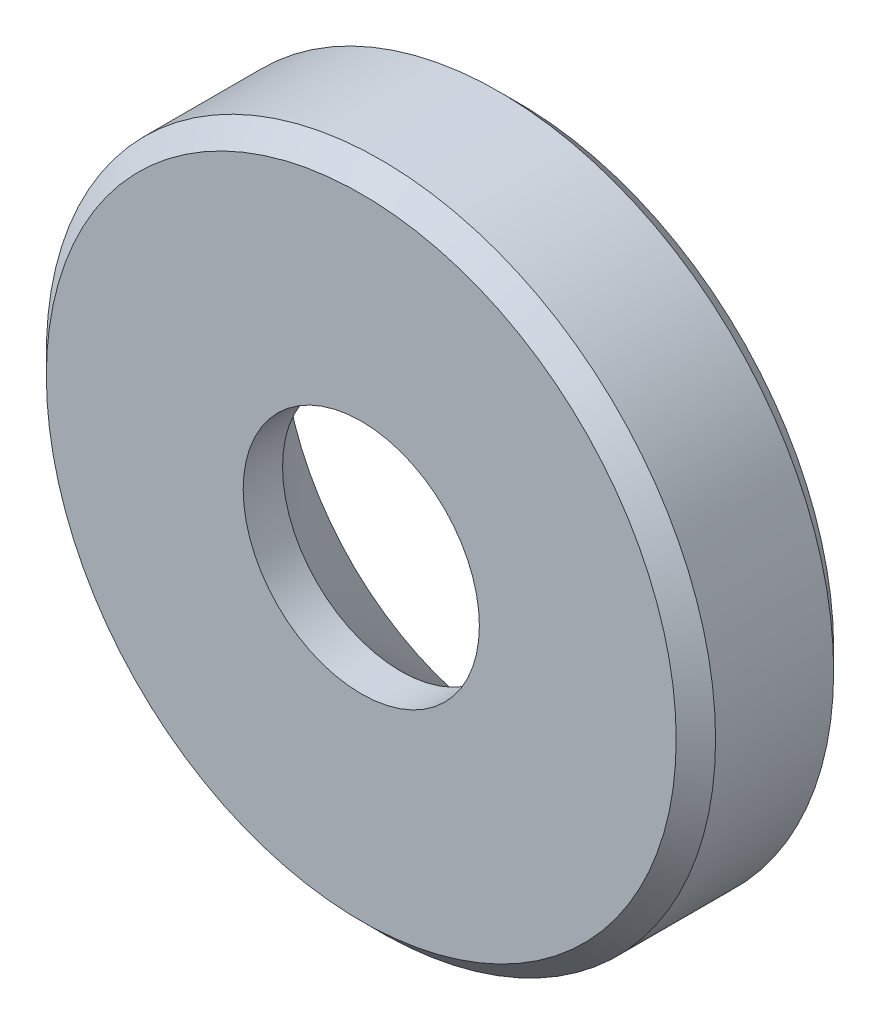
SolidWorks part; units mm, degrees
ref_plane "Front Plane" through (0, 0, 0) normal (0, 0, 1) x (1, 0, 0)
ref_plane "Top Plane" through (0, 0, 0) normal (0, 1, 0) x (1, 0, 0)
ref_plane "Right Plane" through (0, 0, 0) normal (1, 0, 0) x (0, 0, -1)
sketch "Sketch1" plane through (0, 0, 0) normal (0, 0, 1) x (1, 0, 0)
  circle A0 centre (0, 0) radius 17
extrude "Boss-Extrude2" add sketch "Sketch1" along normal blind 8
sketch "Sketch3" plane through (0, 0, 0) normal (0, 1, 0) x (1, 0, 0)
  line L0 (0, 0) -> (0, -8)
  line L1 (-17, -8) -> (17, -8) construction
  line L2 (0, -8) -> (6, -8)
  line L3 (6, -8) -> (6, -6)
  line L4 (6, -6) -> (12, 0)
  line L5 (17, 0) -> (-17, 0) construction
  line L6 (12, 0) -> (0, 0)
  line L7 (0, 0) -> (0, -8) construction
  dimension "D1" = 6
  dimension "D2" = 2
revolve "Cut-Revolve2" cut sketch "Sketch3" angle 360 about L7
chamfer "Chamfer1" distance 1 angle 45 2 edges at (17, 0, 8) (17, 0, 0)
